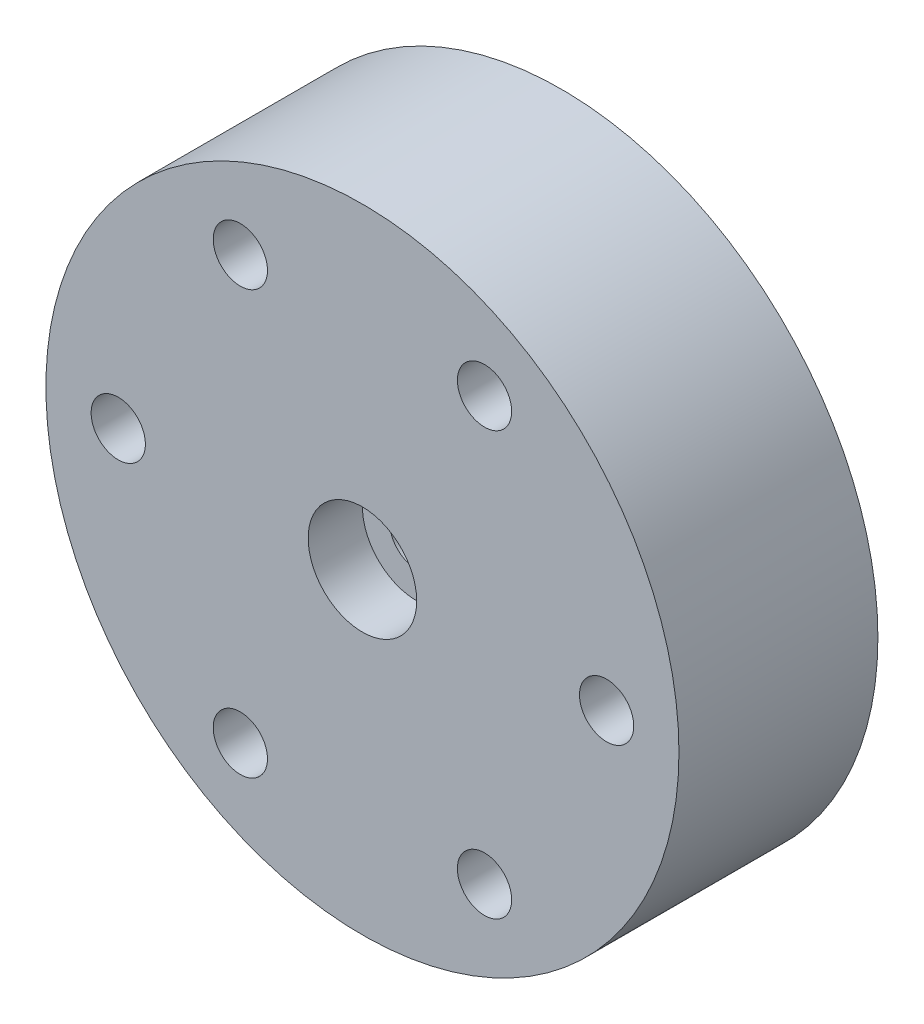
SolidWorks part; units mm, degrees
ref_plane "前视基准面" through (0, 0, 0) normal (0, 0, 1) x (1, 0, 0)
ref_plane "上视基准面" through (0, 0, 0) normal (0, 1, 0) x (1, 0, 0)
ref_plane "右视基准面" through (0, 0, 0) normal (1, 0, 0) x (0, 0, -1)
other "Configuration Table"
sketch "草图1" plane through (0, 0, 0) normal (0, 0, 1) x (1, 0, 0)
  circle A0 centre (0, 0) radius 17.5
  dimension "D1" = 35
extrude "凸台-拉伸1" add sketch "草图1" along normal blind 11
sketch "草图2" plane through (0, 0, 11) normal (0, 0, 1) x (1, 0, 0)
  circle A0 centre (13.5, 0) radius 1.5
  dimension "D1" = 3
  dimension "D2" = 13.5
extrude "切除-拉伸1" cut sketch "草图2" against normal blind 6
pattern_circular "阵列(圆周)1" count 6 over 360 about axis through (0, 0, 0) along (0, 0, 1) of "切除-拉伸1"
sketch "草图3" plane through (0, 0, 11) normal (0, 0, 1) x (1, 0, 0)
  circle A0 centre (0, 0) radius 3
  dimension "D1" = 6
extrude "切除-拉伸2" cut sketch "草图3" against normal blind 3
sketch "草图4" plane through (0, 0, 8) normal (0, 0, 1) x (1, 0, 0)
  circle A0 centre (0, 0) radius 1.5
  dimension "D1" = 3
extrude "切除-拉伸3" cut sketch "草图4" against normal blind 6
